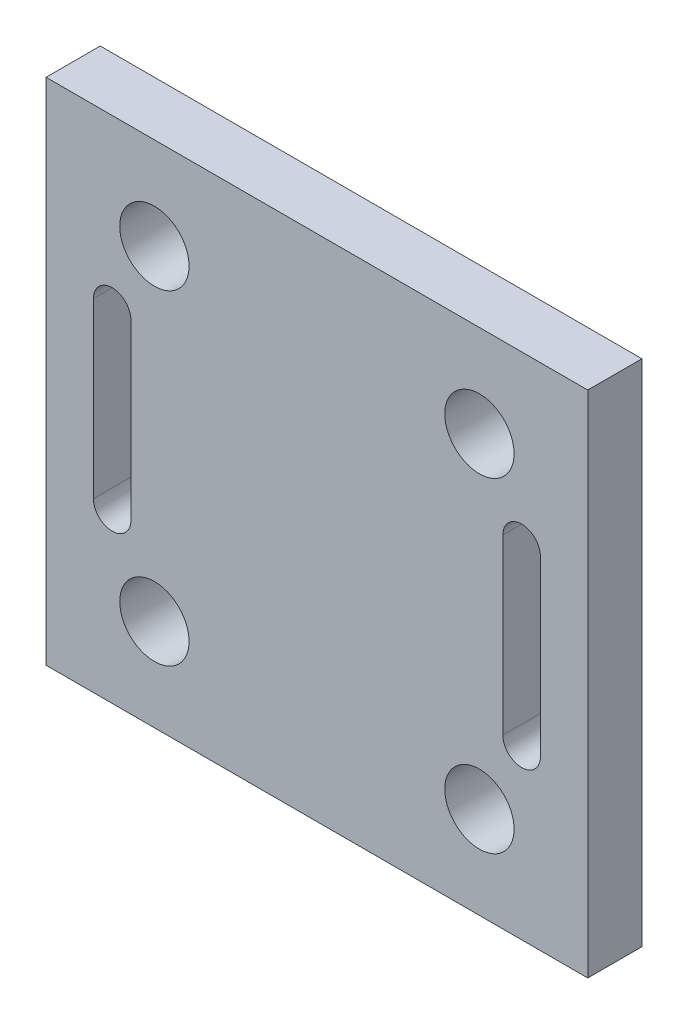
SolidWorks part; units mm, degrees
ref_plane "Front Plane" through (0, 0, 0) normal (0, 0, 1) x (1, 0, 0)
ref_plane "Top Plane" through (0, 0, 0) normal (0, 1, 0) x (1, 0, 0)
ref_plane "Right Plane" through (0, 0, 0) normal (1, 0, 0) x (0, 0, -1)
sketch "Sketch2" plane through (0, 0, 0) normal (0, 0, 1) x (1, 0, 0)
  line L0 (3.875, 14.9225) -> (27.875, 14.9225) construction
  line L1 (0, 0) -> (31.75, 0)
  line L2 (0, 0) -> (0, 29.845)
  line L3 (0, 29.845) -> (31.75, 29.845)
  line L4 (31.75, 0) -> (31.75, 29.845)
  line L5 (6.35, 24.4475) -> (25.4, 24.4475)
  line L6 (6.35, 24.4475) -> (6.35, 5.3975)
  line L7 (6.35, 5.3975) -> (25.4, 5.3975)
  line L8 (25.4, 24.4475) -> (25.4, 5.3975)
  line L9 (3.875, 9.8425) -> (3.875, 20.0025) construction
  line L10 (2.775, 9.8425) -> (2.775, 20.0025)
  line L11 (4.975, 9.8425) -> (4.975, 20.0025)
  line L12 (15.875, 14.9225) -> (15.875, 17.635) construction
  line L13 (27.875, 9.8425) -> (27.875, 20.0025) construction
  line L14 (28.975, 9.8425) -> (28.975, 20.0025)
  line L15 (26.775, 9.8425) -> (26.775, 20.0025)
  arc A0 (2.775, 9.8425) -> (4.975, 9.8425) centre (3.875, 9.8425) ccw
  arc A1 (4.975, 20.0025) -> (2.775, 20.0025) centre (3.875, 20.0025) ccw
  arc A2 (28.975, 9.8425) -> (26.775, 9.8425) centre (27.875, 9.8425) cw
  arc A3 (26.775, 20.0025) -> (28.975, 20.0025) centre (27.875, 20.0025) cw
  point P9 (6.35, 14.9225)
  point P10 (0, 14.9225)
  point P11 (15.875, 24.4475)
  point P12 (15.875, 29.845)
  point P14 (15.875, 14.9225)
  point P18 (3.875, 14.9225)
  point P27 (27.875, 14.9225)
  dimension "D6" = 1.1
  dimension "D1" = 31.75
  dimension "D2" = 29.845
  dimension "D3" = 19.05
  dimension "D4" = 19.05
  dimension "D5" = 24
  dimension "D7" = 10.16
extrude "Boss-Extrude1" add sketch "Sketch2" along normal blind 3.175
hole_wizard "Ø0.16 (4.064) Diameter Hole1" positions "Sketch5" profile "Sketch6" hole size "Ø0.16" standard "ISO" end condition through all
sketch "Sketch5" plane through (0, 0, 0) normal (0, 0, -1) x (-1, 0, 0)
  point P0 (-25.4, 24.4475)
  point P3 (-6.35, 24.4475)
  point P6 (-6.35, 5.3975)
  point P9 (-25.4, 5.3975)
sketch "Sketch6" plane through (25.4, 24.4475, 0) normal (1, 0, 0) x (0, 1, 0)
  line L0 (0, 0) -> (0, 3.175)
  line L1 (0, 3.175) -> (2.032, 3.175)
  line L2 (2.032, 3.175) -> (2.032, 0)
  line L5 (2.032, 0) -> (0, 0)
  line L11 (0, -6.35) -> (0, 107.95) construction
  dimension "Thru Hole Dia." = 4.064
  dimension "Thru Hole Depth" = 3.175
hole_wizard "Ø2.3 (2.3) Diameter Hole2" positions "Sketch7" profile "Sketch8" hole size "Ø2.3" standard "ISO"
sketch "Sketch7" plane through (0, 0, 0) normal (0, 0, -1) x (-1, 0, 0)
  point P0 (-27.875, 14.9225)
  point P3 (-3.875, 14.9225)
sketch "Sketch8" plane through (27.875, 14.9225, 0) normal (1, 0, 0) x (0, 1, 0)
  line L0 (0, 0) -> (0, 3.175)
  line L1 (0, 3.175) -> (1.15, 3.175)
  line L2 (1.15, 3.175) -> (1.15, 0)
  line L5 (1.15, 0) -> (0, 0)
  line L11 (0, -6.35) -> (0, 107.95) construction
  dimension "Thru Hole Dia." = 2.3
  dimension "Thru Hole Depth" = 3.175
